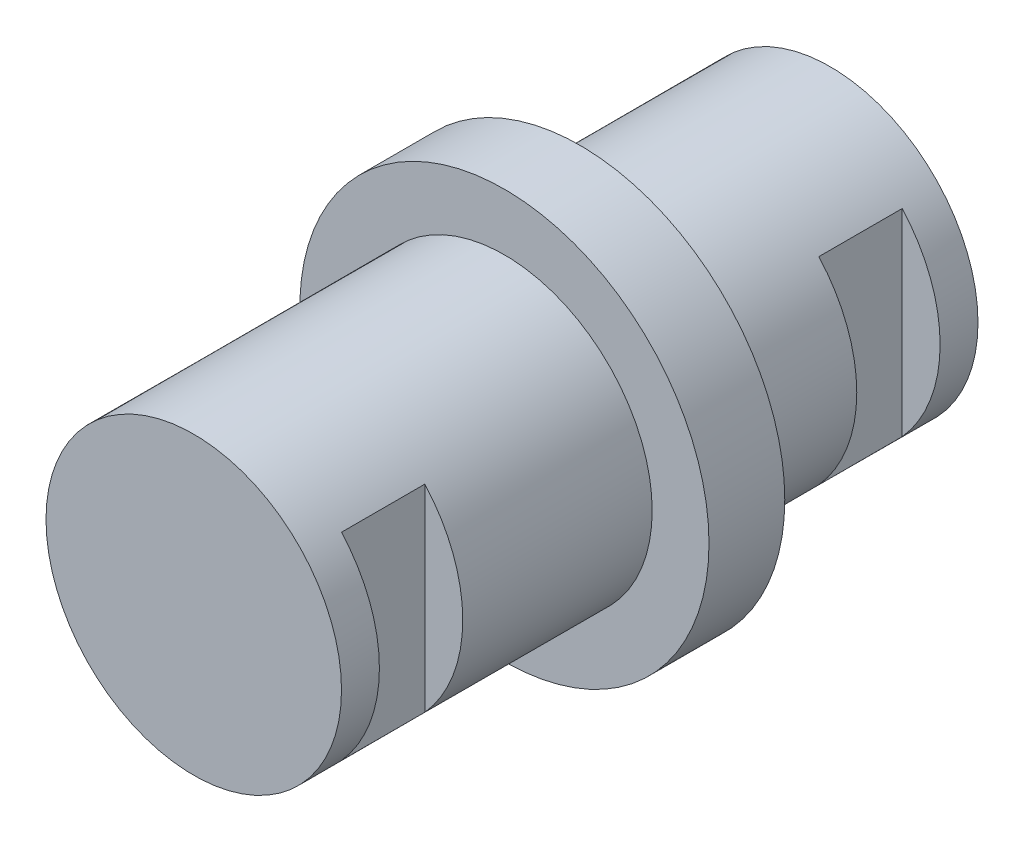
SolidWorks part; units mm, degrees
ref_plane "Front Plane" through (0, 0, 0) normal (0, 0, 1) x (1, 0, 0)
ref_plane "Top Plane" through (0, 0, 0) normal (0, 1, 0) x (1, 0, 0)
ref_plane "Right Plane" through (0, 0, 0) normal (1, 0, 0) x (0, 0, -1)
sketch "Sketch1" plane through (0, 0, 0) normal (0, 0, 1) x (1, 0, 0)
  circle A0 centre (0, 0) radius 4.953
  dimension "D1" = 9.906
extrude "Boss-Extrude1" add sketch "Sketch1" along normal blind 21.336
sketch "Sketch2" plane through (0, 0, 21.336) normal (0, 0, 1) x (1, 0, 0)
  circle A0 centre (0, 0) radius 6.858
  circle A1 centre (0, 0) radius 4.953 construction
  dimension "D1" = 1.905
extrude "Boss-Extrude2" add sketch "Sketch2" against normal blind 2.54 from offset 10.414 offset against normal yes
sketch "Sketch3" plane through (0, 0, 0) normal (0, 1, 0) x (1, 0, 0)
  line L0 (-4.953, 0) -> (-4.953, -8.382) construction
  line L1 (-4.953, -1.27) -> (4.953, -1.27)
  line L2 (-4.953, -1.27) -> (-4.953, -4.064)
  line L3 (-4.953, -4.064) -> (4.953, -4.064)
  line L4 (4.953, -1.27) -> (4.953, -4.064)
  line L5 (4.953, -8.382) -> (4.953, 0) construction
  line L6 (4.953, 0) -> (-4.953, 0) construction
  line L7 (-3.683, -1.27) -> (3.683, -1.27)
  line L8 (-3.683, -1.27) -> (-3.683, -4.064)
  line L9 (-3.683, -4.064) -> (3.683, -4.064)
  line L10 (3.683, -1.27) -> (3.683, -4.064)
  dimension "D1" = 1.27
  dimension "D2" = 2.794
  dimension "D3" = 1.27
  dimension "D4" = 1.27
extrude "Cut-Extrude1" cut sketch "Sketch3" against normal through all and the other way through all contours L1 L10 L3 L4 | L8 L1 L2 L3
sketch "Sketch4" plane through (0, 0, 0) normal (0, 1, 0) x (1, 0, 0)
  line L0 (-4.953, -17.272) -> (4.953, -17.272)
  line L1 (-4.953, -17.272) -> (-4.953, -20.066)
  line L2 (-4.953, -20.066) -> (4.953, -20.066)
  line L3 (4.953, -17.272) -> (4.953, -20.066)
  line L4 (-3.683, -17.272) -> (3.683, -17.272)
  line L5 (-3.683, -17.272) -> (-3.683, -20.066)
  line L6 (-3.683, -20.066) -> (3.683, -20.066)
  line L7 (3.683, -17.272) -> (3.683, -20.066)
  line L8 (-4.953, -21.336) -> (4.953, -21.336) construction
  line L9 (4.953, -21.336) -> (4.953, -10.922) construction
  line L10 (-4.953, -10.922) -> (-4.953, -21.336) construction
  dimension "D1" = 2.794
  dimension "D2" = 1.27
  dimension "D3" = 1.27
  dimension "D4" = 1.27
  dimension "D5" = 0
  dimension "D6" = 0
extrude "Cut-Extrude2" cut sketch "Sketch4" against normal through all and the other way through all contours L0 L7 L2 L3 | L5 L0 L1 L2
